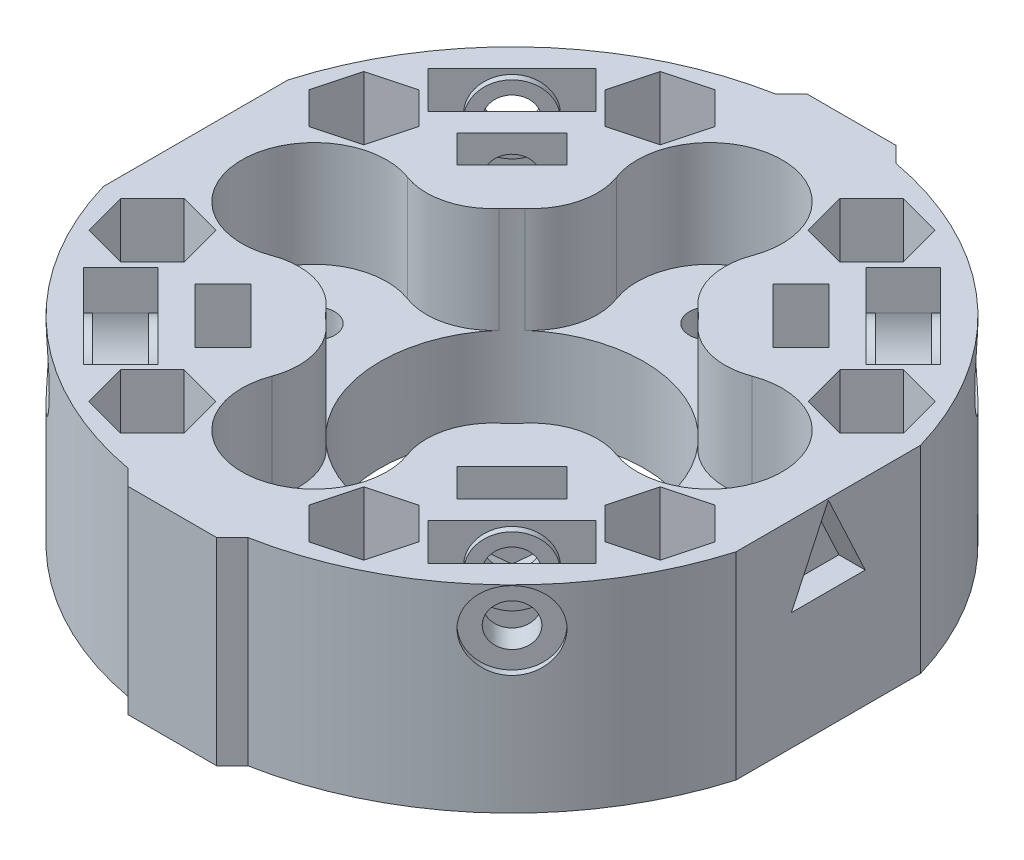
SolidWorks part; units mm, degrees
ref_plane "Alzado" through (0, 0, 0) normal (0, 0, 1) x (1, 0, 0)
ref_plane "Planta" through (0, 0, 0) normal (0, 1, 0) x (1, 0, 0)
ref_plane "Vista lateral" through (0, 0, 0) normal (1, 0, 0) x (0, 0, -1)
sketch "Croquis1" plane through (0, 0, 0) normal (0, 1, 0) x (1, 0, 0)
  line L0 (-3.36, 25.77) -> (-4.5504, 24.5824)
  line L1 (-4.5504, 24.5824) -> (-3.36, 25.77)
  line L3 (-3.36, 25.77) -> (3.36, 25.77)
  line L4 (3.36, 25.77) -> (4.5436, 24.5837)
  line L5 (0, -77.7733) -> (0, 77.7733) construction
  line L6 (0, 0) -> (18.4151, 0) construction
  line L7 (-3.36, 25.77) -> (-4.5436, 24.5837)
  line L8 (4.5504, 24.5824) -> (3.36, 25.77)
  line L9 (3.36, 25.77) -> (4.5504, 24.5824)
  line L10 (-3.36, 25.77) -> (-4.5504, 24.5824)
  line L11 (-4.5504, 24.5824) -> (-3.36, 25.77)
  line L12 (3.36, 25.77) -> (4.5436, 24.5837)
  line L13 (-3.36, 25.77) -> (-4.5436, 24.5837)
  line L14 (4.5504, 24.5824) -> (3.36, 25.77)
  line L15 (3.36, 25.77) -> (4.5504, 24.5824)
  line L16 (3.36, -25.77) -> (4.5504, -24.5824)
  line L17 (4.5504, -24.5824) -> (3.36, -25.77)
  line L18 (-3.36, -25.77) -> (-4.5436, -24.5837)
  line L19 (3.36, -25.77) -> (4.5436, -24.5837)
  line L20 (-4.5504, -24.5824) -> (-3.36, -25.77)
  line L21 (-3.36, -25.77) -> (-4.5504, -24.5824)
  line L22 (3.36, -25.77) -> (4.5504, -24.5824)
  line L23 (4.5504, -24.5824) -> (3.36, -25.77)
  line L24 (-3.36, -25.77) -> (-4.5436, -24.5837)
  line L25 (3.36, -25.77) -> (4.5436, -24.5837)
  line L26 (-3.36, -25.77) -> (3.36, -25.77)
  line L27 (-4.5504, -24.5824) -> (-3.36, -25.77)
  line L28 (-3.36, -25.77) -> (-4.5504, -24.5824)
  line L29 (24, 7) -> (24, -7)
  line L31 (-24, -7) -> (-24, 7)
  arc A0 (-4.5504, 24.5824) -> (-24, 7) centre (0, 0) ccw
  arc A1 (4.5504, 24.5824) -> (24, 7) centre (0, 0) cw
  arc A2 (-4.5504, 24.5824) -> (-24, 7) centre (0, 0) ccw
  arc A3 (4.5504, 24.5824) -> (24, 7) centre (0, 0) cw
  arc A4 (4.5504, -24.5824) -> (24, -7) centre (0, 0) ccw
  arc A5 (-4.5504, -24.5824) -> (-24, -7) centre (0, 0) cw
  arc A6 (4.5504, -24.5824) -> (24, -7) centre (0, 0) ccw
  arc A7 (-4.5504, -24.5824) -> (-24, -7) centre (0, 0) cw
  arc A8 (-24, -7) -> (24, -7) centre (0, 0) ccw
  arc A9 (-24, 7) -> (-4.5436, 24.5837) centre (0, 0) cw
  arc A10 (-24, -7) -> (24, -7) centre (0, 0) ccw
  arc A11 (-24, 7) -> (-4.5436, 24.5837) centre (0, 0) cw
  arc A12 (-24, -7) -> (-4.5436, -24.5837) centre (0, 0) ccw
  arc A13 (-24, 7) -> (24, 7) centre (0, 0) cw
  arc A14 (-24, -7) -> (-4.5436, -24.5837) centre (0, 0) ccw
  arc A15 (-24, 7) -> (24, 7) centre (0, 0) cw
  arc A16 (24, -7) -> (-24, -7) centre (0, 0) cw
  arc A17 (24, -7) -> (-24, -7) centre (0, 0) cw
  arc A18 (24, 7) -> (-24, 7) centre (0, 0) ccw
  arc A19 (24, 7) -> (-24, 7) centre (0, 0) ccw
  arc A20 (24, 7) -> (4.5436, 24.5837) centre (0, 0) ccw
  arc A21 (24, 7) -> (4.5436, 24.5837) centre (0, 0) ccw
  arc A22 (24, -7) -> (4.5436, -24.5837) centre (0, 0) cw
  arc A23 (24, -7) -> (4.5436, -24.5837) centre (0, 0) cw
  point P17 (0, 25.77)
  dimension "D1" = 3.36
  dimension "D2" = 9.094
  dimension "D3" = 4.5436
  dimension "D4" = 25.77
  dimension "D5" = 24
  dimension "D6" = 24
extrude "Saliente-Extruir1" add sketch "Croquis1" along normal blind 15
ref_plane "Plano1" through (0, 0, 0) normal (-0.7071, 0, 0.7071) x (0.7071, 0, 0.7071)
ref_plane "Plano2" through (16.2635, 0, -16.2635) normal (-0.7071, 0, 0.7071) x (0.7071, 0, 0.7071)
sketch "Croquis3" plane through (16.2635, 0, -16.2635) normal (-0.7071, 0, 0.7071) x (0.7071, 0, 0.7071)
  line L0 (-25, 15) -> (25, 15) construction
  line L1 (0, 0) -> (0, 15) construction
  line L3 (12.0208, 15) -> (-14.1705, 15) construction
  line L4 (25, 15) -> (25, -8.8122) construction
  line L6 (-4.5, 12) -> (-4.5, 15)
  line L7 (-4.5, 15) -> (4.5, 15)
  line L8 (4.5, 12) -> (4.5, 15)
  line L9 (25, 0) -> (25, 15) construction
  arc A0 (-4.5, 12) -> (4.5, 12) centre (0, 12) ccw
  circle A1 centre (0, 12) radius 4 construction
  point P11 (0, 15)
  dimension "D1" = 4.5
  dimension "D2" = 8
  dimension "D3" = 3
  dimension "D4" = 50
extrude "Cortar-Extruir1" cut sketch "Croquis3" along normal blind 4
ref_plane "Plano3" through (12.0208, 0, -12.0208) normal (0.7071, 0, -0.7071) x (-0.7071, 0, -0.7071)
sketch "Croquis4" plane through (12.0208, 0, -12.0208) normal (0.7071, 0, -0.7071) x (-0.7071, 0, -0.7071)
  line L0 (-4.5, 15) -> (4.5, 15) construction
  line L1 (-2.95, 10.2968) -> (0, 8.5936)
  line L2 (0, 8.5936) -> (2.95, 10.2968)
  line L3 (2.95, 10.2968) -> (2.95, 13.7032)
  line L4 (2.95, 13.7032) -> (0, 15.4064) construction
  line L5 (0, 15.4064) -> (-2.95, 13.7032) construction
  line L6 (-2.95, 13.7032) -> (-2.95, 10.2968)
  line L8 (-2.95, 13.7032) -> (-2.95, 15)
  line L9 (-2.95, 15) -> (2.95, 15)
  line L10 (2.95, 13.7032) -> (2.95, 15)
  circle A0 centre (0, 12) radius 2.95 construction
  arc A1 (-4.5, 12) -> (4.5, 12) centre (0, 12) ccw construction
  dimension "D1" = 5.9
extrude "Cortar-Extruir2" cut sketch "Croquis4" against normal blind 3
sketch "Croquis5" plane through (12.0208, 0, -12.0208) normal (-0.7071, 0, 0.7071) x (0.7071, 0, 0.7071)
  circle A0 centre (0, 12) radius 1.6
  arc A2 (-4.5, 12) -> (4.5, 12) centre (0, 12) ccw construction
  dimension "D1" = 3.2
extrude "Cortar-Extruir3" cut sketch "Croquis5" against normal through all
sketch "Croquis6" plane through (24, 0, 0) normal (1, 0, 0) x (0, 0, -1)
  line L0 (0, 14.9) -> (-2.8, 8.9)
  line L1 (-2.8, 8.9) -> (2.8, 8.9)
  line L2 (2.8, 8.9) -> (0, 14.9)
  line L3 (0, 15) -> (0, 0) construction
  line L4 (7, 0) -> (-7, 0) construction
  line L5 (7, 15) -> (-7, 15) construction
  point P10 (0, 15)
  point P12 (0, 8.9)
  dimension "D1" = 6
  dimension "D2" = 5.6
  dimension "D3" = 0.1
extrude "Cortar-Extruir4" cut sketch "Croquis6" against normal blind 2
ref_plane "Plano4" through (19.4454, 0, -19.4454) normal (0.7071, 0, -0.7071) x (-0.7071, 0, -0.7071)
sketch "Croquis8" plane through (19.4454, 0, -19.4454) normal (0.7071, 0, -0.7071) x (-0.7071, 0, -0.7071)
  circle A0 centre (0, 12) radius 2.95
  circle A1 centre (0, 12) radius 1.6 construction
  dimension "D1" = 5.9
extrude "Cortar-Extruir5" cut sketch "Croquis8" against normal blind 3
sketch "Croquis10" plane through (13.435, 0, -13.435) normal (0.7071, 0, -0.7071) x (-0.7071, 0, -0.7071)
  circle A0 centre (0, 12) radius 2.6
  circle A1 centre (0, 12) radius 1.6 construction
  circle A2 centre (0, 12) radius 1.6
  dimension "D1" = 1
extrude "Saliente-Extruir2" add sketch "Croquis10" along normal blind 0.5
sketch "Croquis11" plane through (16.2635, 0, -16.2635) normal (-0.7071, 0, 0.7071) x (0.7071, 0, 0.7071)
  circle A0 centre (0, 12) radius 1.6
  circle A1 centre (0, 12) radius 1.6 construction
  circle A2 centre (0, 12) radius 2.6
  circle A3 centre (0, 12) radius 2.6 construction
extrude "Saliente-Extruir3" add sketch "Croquis11" along normal blind 0.5
sketch "Croquis12" plane through (0, 0, 0) normal (0, -1, 0) x (1, 0, 0)
  line L0 (0, -15) -> (0, 0) construction
  line L1 (-15, 0) -> (0, 0) construction
  line L2 (0, 15) -> (0, 0) construction
  line L3 (15, 0) -> (0, 0) construction
  circle A0 centre (0, 0) radius 10
  circle A1 centre (0, -15) radius 1.55
  circle A4 centre (-15, 0) radius 1.55
  circle A5 centre (0, 15) radius 1.55
  circle A6 centre (15, 0) radius 1.55
  point P15 (0, 0)
  dimension "D1" = 20
  dimension "D2" = 3.1
  dimension "D3" = 15
extrude "Cortar-Extruir6" cut sketch "Croquis12" against normal through all
sketch "Croquis13" plane through (0, 15, 0) normal (0, 1, 0) x (1, 0, 0)
  line L0 (0, 15) -> (0, 0) construction
  line L1 (15, 0) -> (0, 0) construction
  line L2 (0, -15) -> (0, 0) construction
  line L3 (-15, 0) -> (0, 0) construction
  arc A0 (13.075, -5.1521) -> (7.55, -6.5572) centre (11.325, -9.8359) ccw
  arc A1 (-6.5572, 7.55) -> (6.5572, 7.55) centre (0, 0) ccw
  arc A2 (5.1521, 13.075) -> (6.5572, 7.55) centre (9.8359, 11.325) ccw
  arc A3 (-5.1521, 13.075) -> (-6.5572, 7.55) centre (-9.8359, 11.325) cw
  arc A4 (13.075, 5.1521) -> (7.55, 6.5572) centre (11.325, 9.8359) cw
  arc A5 (5.1521, 13.075) -> (-5.1521, 13.075) centre (0, 15) ccw
  arc A6 (13.075, -5.1521) -> (13.075, 5.1521) centre (15, 0) ccw
  arc A7 (-5.1521, -13.075) -> (-6.5572, -7.55) centre (-9.8359, -11.325) ccw
  arc A8 (5.1521, -13.075) -> (6.5572, -7.55) centre (9.8359, -11.325) cw
  arc A9 (-5.1521, -13.075) -> (5.1521, -13.075) centre (0, -15) ccw
  arc A10 (-13.075, 5.1521) -> (-7.55, 6.5572) centre (-11.325, 9.8359) ccw
  arc A11 (-13.075, -5.1521) -> (-7.55, -6.5572) centre (-11.325, -9.8359) cw
  arc A12 (-13.075, 5.1521) -> (-13.075, -5.1521) centre (-15, 0) ccw
  point P33 (0, 0)
  circle M1 centre (15, 0) radius 1.55
  circle M2 centre (0, -15) radius 1.55
  circle M3 centre (-15, 0) radius 1.55
  circle M4 centre (0, 15) radius 1.55
  circle M5 centre (0, 0) radius 10
  dimension "D1" = 5.5
  dimension "D3" = 20
  dimension "D4" = 5
  dimension "D5" = 5
  dimension "D2" = 15
extrude "Cortar-Extruir7" cut sketch "Croquis13" against normal blind 8 contours A2 A5 A3 M5 M4 | A1 M5 | A7 A9 A8 A1 M2 | A10 A12 A11 M5 M3 | A0 A6 A4 A1 M1
pattern_circular "MatrizC1" count 4 every 90 about axis through (0, 0, 0) along (0, 1, 0) of "Cortar-Extruir5", "Cortar-Extruir3", "Saliente-Extruir2", "Cortar-Extruir1", "Cortar-Extruir2", "Saliente-Extruir3"
sketch "Croquis14" plane through (0, 0, 0) normal (0, -1, 0) x (1, 0, 0)
  circle A0 centre (0, -15) radius 2.95
  dimension "D1" = 5.9
extrude "Cortar-Extruir8" cut sketch "Croquis14" against normal blind 3
pattern_circular "MatrizC2" count 4 every 90 about axis through (0, 0, 0) along (0, 1, 0) of "Cortar-Extruir8"
sketch "Croquis15" plane through (0, 0, 0) normal (0, -1, 0) x (1, 0, 0)
  line L0 (0, 0) -> (-10.6066, 10.6066) construction
  line L1 (-10.6066, 10.6066) -> (0, 0) construction
  line L2 (0, 0) -> (0, 17.95) construction
  circle A0 centre (-10.6066, 10.6066) radius 1.5
  circle A1 centre (0, 15) radius 2.95 construction
  dimension "D1" = 3
  dimension "D2" = 45
  dimension "D3" = 15
extrude "Cortar-Extruir9" cut sketch "Croquis15" against normal blind 5
pattern_circular "MatrizC3" count 4 every 90 about axis through (0, 0, 0) along (0, 1, 0) of "Cortar-Extruir9"
sketch "Croquis16" plane through (0, 15, 0) normal (0, 1, 0) x (1, 0, 0)
  line L0 (-10.253, 16.617) -> (-13.0815, 19.4454) construction
  line L1 (-4.7331, 20.148) -> (-7.1418, 22.5567)
  line L2 (-7.1418, 22.5567) -> (-10.4321, 21.6751)
  line L3 (-10.4321, 21.6751) -> (-11.3137, 18.3848)
  line L4 (-11.3137, 18.3848) -> (-8.905, 15.9761)
  line L5 (-8.905, 15.9761) -> (-5.6147, 16.8577)
  line L6 (-5.6147, 16.8577) -> (-4.7331, 20.148)
  line L7 (-13.0815, 19.4454) -> (-19.4454, 13.0815) construction
  line L8 (-16.617, 10.253) -> (-19.4454, 13.0815) construction
  line L9 (-18.3848, 11.3137) -> (-21.6751, 10.4321)
  line L10 (-21.6751, 10.4321) -> (-22.5567, 7.1418)
  line L11 (-22.5567, 7.1418) -> (-20.148, 4.7331)
  line L12 (-20.148, 4.7331) -> (-16.8577, 5.6147)
  line L13 (-16.8577, 5.6147) -> (-15.9761, 8.905)
  line L14 (-15.9761, 8.905) -> (-18.3848, 11.3137)
  circle A0 centre (-8.0234, 19.2664) radius 2.95 construction
  circle A1 centre (-8.0234, 19.2664) radius 1.6
  circle A2 centre (-19.2664, 8.0234) radius 2.95 construction
  circle A3 centre (-19.2664, 8.0234) radius 1.6
  dimension "D4" = 3.2
  dimension "D8" = 3.2
  dimension "D1" = 0.5
  dimension "D2" = 5.9
  dimension "D3" = 2
  dimension "D5" = 0.5
  dimension "D6" = 2
  dimension "D7" = 5.9
extrude "Cortar-Extruir10" cut sketch "Croquis16" against normal blind 10
sketch "Croquis17" plane through (0, 15, 0) normal (0, 1, 0) x (1, 0, 0)
  circle A0 centre (-19.2664, 8.0234) radius 1.6 construction
  circle A1 centre (-8.0234, 19.2664) radius 1.6 construction
  circle A2 centre (-19.2664, 8.0234) radius 1.6
  circle A3 centre (-8.0234, 19.2664) radius 1.6
extrude "Cortar-Extruir11" cut sketch "Croquis17" against normal through all
pattern_circular "MatrizC4" count 4 every 90 about axis through (0, 0, 0) along (0, 1, 0) of "Cortar-Extruir10", "Cortar-Extruir11"
